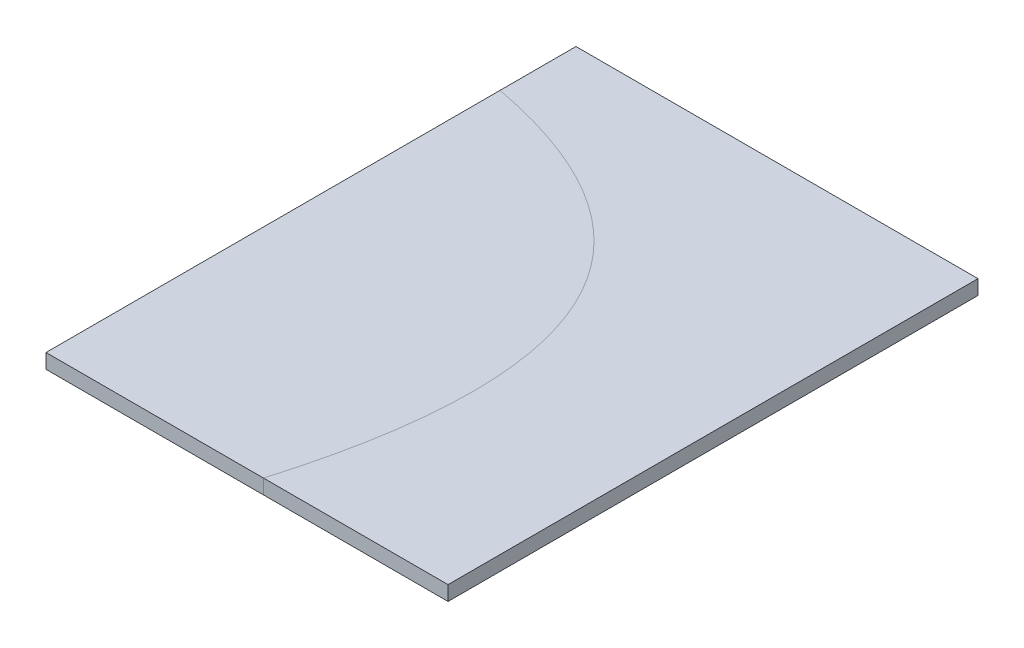
SolidWorks part; units mm, degrees
ref_plane "Front Plane" through (0, 0, 0) normal (0, 0, 1) x (1, 0, 0)
ref_plane "Top Plane" through (0, 0, 0) normal (0, 1, 0) x (1, 0, 0)
ref_plane "Right Plane" through (0, 0, 0) normal (1, 0, 0) x (0, 0, -1)
sketch "Sketch1" plane through (0, 0, 0) normal (0, 1, 0) x (1, 0, 0)
  line L1 (-617.7778, 963.3333) -> (482.2222, 963.3333)
  line L2 (-617.7778, 963.3333) -> (-617.7778, -486.6667)
  line L3 (-617.7778, -486.6667) -> (482.2222, -486.6667)
  line L4 (482.2222, 963.3333) -> (482.2222, -486.6667)
  dimension "D1" = 1100
  dimension "D2" = 1450
extrude "Boss-Extrude1" add sketch "Sketch1" along normal blind 40
sketch "Sketch2" plane through (0, 0, 0) normal (0, -1, 0) x (1, 0, 0)
  line L0 (482.2222, 486.6667) -> (482.2222, -963.3333) construction
  line L1 (-617.7778, 486.6667) -> (482.2222, 486.6667) construction
  circle A0 centre (217.2222, 221.6667) radius 50
  circle A1 centre (217.2222, 221.6667) radius 70
  dimension "D3" = 100
  dimension "D1" = 265
  dimension "D2" = 265
  dimension "D4" = 20
extrude "Boss-Extrude2" add sketch "Sketch2" along normal blind 40
sketch "Sketch6" plane through (0, 0, 0) normal (0, -1, 0) x (1, 0, 0)
  line L3 (-617.7778, 486.6667) -> (482.2222, 486.6667) construction
  line L4 (-617.7778, -963.3333) -> (-617.7778, 486.6667) construction
  line L17 (-617.7778, -238.3333) -> (-617.7778, -755.5864)
  line L18 (-617.7778, 486.6667) -> (-617.7778, -238.3333)
  line L19 (-22.6208, 486.6667) -> (-617.7778, 486.6667)
  spline S1 degree 2 poles (-22.6208, 486.6667) (293.4326, -583.781) (-617.7778, -755.5864) knots 0 0 0 1 1 1
  point P0 (-571.3282, 455.7037)
  dimension "D6" = 1616.0457
  dimension "D1" = 0
  dimension "D2" = 0
  dimension "D3" = 595.157
  dimension "D4" = 1242.253
  dimension "D5" = 725
extrude "Cut-Extrude1" cut sketch "Sketch6" against normal blind 1020
sketch "Sketch8" plane through (0, 0, 0) normal (0, -1, 0) x (1, 0, 0)
  line L3 (-22.6208, 486.6667) -> (-617.7778, 486.6667)
  line L4 (-617.7778, 486.6667) -> (-617.7778, -755.5864)
  parabola Q2 (-617.7778, -755.5864) -> (-22.6208, 486.6667) focus (-314.6268, -278.4877) apex (-71.555, -456.4727)
  parabola Q3 (-617.7778, -755.5864) -> (-22.6208, 486.6667) focus (-314.6268, -278.4877) apex (-71.555, -456.4727)
  dimension "D1" = 0
extrude "Boss-Extrude3" add sketch "Sketch8" against normal blind 40 separate body
